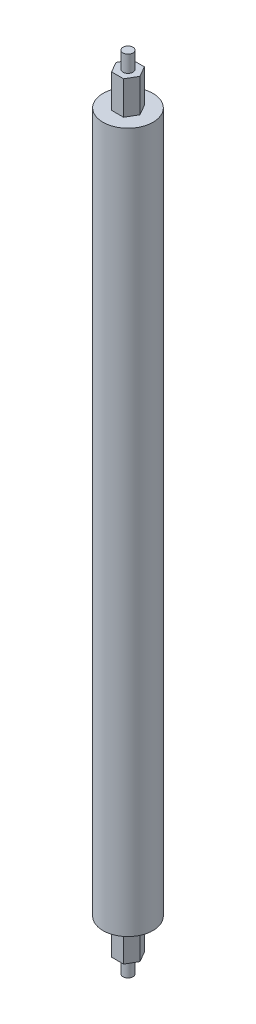
SolidWorks part; units mm, degrees
ref_plane "Front Plane" through (0, 0, 0) normal (0, 0, 1) x (1, 0, 0)
ref_plane "Top Plane" through (0, 0, 0) normal (0, 1, 0) x (1, 0, 0)
ref_plane "Right Plane" through (0, 0, 0) normal (1, 0, 0) x (0, 0, -1)
sketch "Sketch2" plane through (0, 0, 0) normal (0, 1, 0) x (1, 0, 0)
  circle A0 centre (0, 0) radius 7.5
  dimension "D1" = 15
extrude "Boss-Extrude1" add sketch "Sketch2" along normal blind 240 contours A0
sketch "Sketch3" plane through (0, 240, 0) normal (0, 1, 0) x (1, 0, 0)
  circle A0 centre (0, 0) radius 7.5
  circle A1 centre (0, 0) radius 1.5
  dimension "D1" = 15
  dimension "D2" = 3
extrude "Cut-Extrude1" cut sketch "Sketch3" against normal blind 15
sketch "Sketch4" plane through (0, 225, 0) normal (0, 1, 0) x (1, 0, 0)
  line L0 (-1.8, 3.1177) -> (1.8, 3.1177)
  line L1 (1.8, 3.1177) -> (3.6, 0)
  line L2 (3.6, 0) -> (1.8, -3.1177)
  line L3 (1.8, -3.1177) -> (-1.8, -3.1177)
  line L4 (-1.8, -3.1177) -> (-3.6, 0)
  line L5 (-3.6, 0) -> (-1.8, 3.1177)
  line L6 (0, 3.1177) -> (0, -3.1177) construction
  point P3 (0, 0)
  point P9 (0, 0)
  point P11 (0, -3.1177)
  dimension "D1" = 3.6
  dimension "D2" = 120
  dimension "D3" = 120
extrude "Boss-Extrude2" add sketch "Sketch4" along normal blind 10
ref_plane "Plane1" through (0, 120, 0) normal (0, 1, 0) x (1, 0, 0)
mirror "Mirror1" about plane through (0, 120, 0) normal (0, 1, 0) of "Boss-Extrude2", "Cut-Extrude1"
